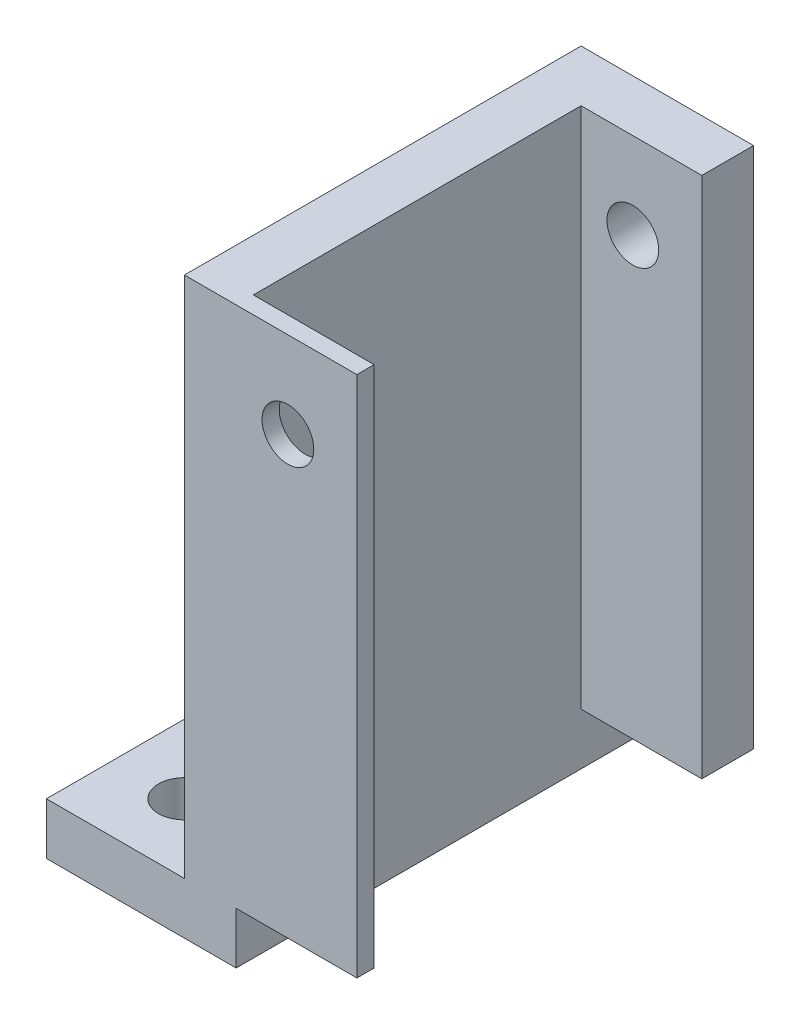
SolidWorks part; units mm, degrees
ref_plane "Alzado" through (0, 0, 0) normal (0, 0, 1) x (1, 0, 0)
ref_plane "Planta" through (0, 0, 0) normal (0, 1, 0) x (1, 0, 0)
ref_plane "Vista lateral" through (0, 0, 0) normal (1, 0, 0) x (0, 0, -1)
sketch "Croquis1" plane through (0, 0, 0) normal (1, 0, 0) x (0, 0, -1)
  line L1 (-23, 0) -> (0, 0)
  line L2 (-23, 0) -> (-23, -30.3)
  line L3 (-23, -30.3) -> (0, -30.3)
  line L4 (0, 0) -> (0, -30.3)
  dimension "D1" = 30.3
  dimension "D2" = 23
extrude "Saliente-Extruir2" add sketch "Croquis1" along normal blind 10
sketch "Croquis3" plane through (0, 0, 0) normal (0, 1, 0) x (1, 0, 0)
  line L0 (10, 0) -> (10, -23) construction
  line L1 (10, -3) -> (3, -3)
  line L2 (10, -3) -> (10, -22)
  line L3 (10, -22) -> (3, -22)
  line L4 (3, -3) -> (3, -22)
  line L5 (10, 0) -> (0, 0) construction
  line L6 (10, -23) -> (0, -23) construction
  line L7 (0, 0) -> (0, -23) construction
  dimension "D1" = 3
  dimension "D2" = 1
  dimension "D3" = 3
extrude "Cortar-Extruir1" cut sketch "Croquis3" against normal through all
sketch "Croquis4" plane through (0, -30.3, 0) normal (0, -1, 0) x (1, 0, 0)
  line L0 (10, 23) -> (0, 23) construction
  line L1 (3, 23) -> (-8, 23)
  line L2 (3, 23) -> (3, 0)
  line L3 (3, 0) -> (-8, 0)
  line L4 (-8, 23) -> (-8, 0)
  line L5 (3, 3) -> (3, 22) construction
  line L6 (10, 0) -> (0, 0) construction
  dimension "D1" = 11
extrude "Saliente-Extruir3" add sketch "Croquis4" along normal blind 3
sketch "Croquis5" plane through (0, -30.3, 0) normal (0, 1, 0) x (1, 0, 0)
  line L0 (-8, -23) -> (-8, 0) construction
  line L2 (-8, 0) -> (0, 0) construction
  line L3 (0, -23) -> (-8, -23) construction
  circle A0 centre (-4, -4) radius 1.5
  circle A1 centre (-4, -19) radius 1.5
  dimension "D1" = 3
  dimension "D2" = 3
  dimension "D3" = 4
  dimension "D4" = 4
  dimension "D5" = 4
  dimension "D6" = 4
extrude "Cortar-Extruir3" cut sketch "Croquis5" against normal through all contours A0 | A1
sketch "Croquis6" plane through (0, 0, 23) normal (0, 0, 1) x (1, 0, 0)
  line L0 (10, 0) -> (10, -30.3) construction
  line L1 (10, 0) -> (0, 0) construction
  circle A0 centre (6, -5) radius 1.5
  dimension "D1" = 3
  dimension "D2" = 4
  dimension "D3" = 5
extrude "Cortar-Extruir4" cut sketch "Croquis6" against normal through all
ref_plane "Plano6" through (0, 0, 11.5) normal (0, 0, 1) x (1, 0, 0)
sketch "Croquis23" plane through (0, 0, 11.5) normal (0, 0, 1) x (1, 0, 0)
  line L0 (-4.9497, -30.3) -> (0, -25.3503)
  line L1 (0, -30.3) -> (-8, -30.3) construction
  line L2 (0, 0) -> (0, -30.3) construction
  dimension "D1" = 45
  dimension "D2" = 7
rib "Nervio10" sketch "Croquis23" sketch "Croquis23" thickness 7 extrusion direction parallel to sketch draft on no parameters "D1"=7
